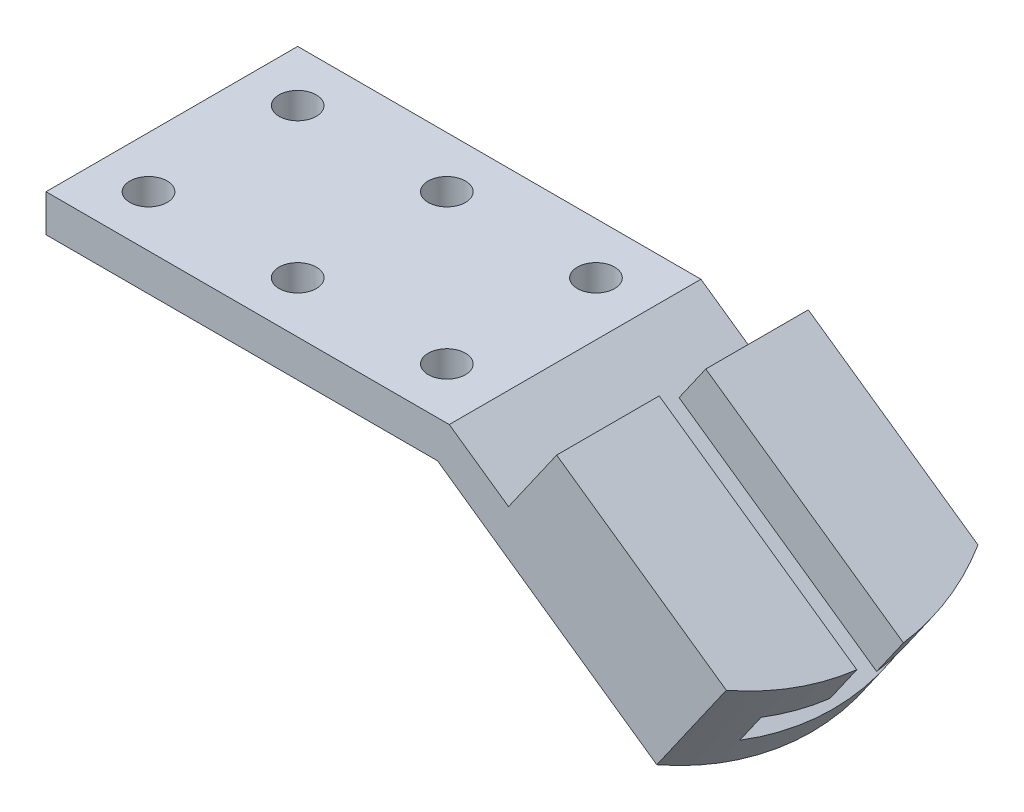
SolidWorks part; units mm, degrees
ref_plane "Front Plane" through (0, 0, 0) normal (0, 0, 1) x (1, 0, 0)
ref_plane "Top Plane" through (0, 0, 0) normal (0, 1, 0) x (1, 0, 0)
ref_plane "Right Plane" through (0, 0, 0) normal (1, 0, 0) x (0, 0, -1)
sketch "Sketch1" plane through (0, 0, 0) normal (0, 0, 1) x (1, 0, 0)
  line L0 (0, 0) -> (84, 0)
  line L1 (84, 0) -> (137.2449, -37.2825)
  line L2 (137.2449, -37.2825) -> (152.1579, -15.9845)
  line L3 (152.1579, -15.9845) -> (109.562, 13.8415)
  line L4 (109.562, 13.8415) -> (99.2376, -0.9033)
  line L5 (99.2376, -0.9033) -> (86.5224, 8)
  line L6 (86.5224, 8) -> (0, 8)
  line L7 (0, 8) -> (0, 0)
  point P3 (104.3998, 6.4691)
  dimension "D1" = 84
  dimension "D2" = 55
  dimension "D3" = 65
  dimension "D4" = 26
  dimension "D5" = 8
  dimension "D6" = 52
  dimension "D7" = 8
extrude "Boss-Extrude1" add sketch "Sketch1" along normal mid plane 54
sketch "Sketch2" plane through (0, 8, 0) normal (0, 1, 0) x (1, 0, 0)
  line L0 (86.5224, 27) -> (0, 27) construction
  line L1 (0, -27) -> (0, 27) construction
  line L2 (86.5224, -27) -> (0, -27) construction
  circle A0 centre (11, 16) radius 4
  circle A1 centre (43, 16) radius 4
  circle A2 centre (75, 16) radius 4
  circle A3 centre (43, -16) radius 4
  circle A4 centre (75, -16) radius 4
  circle A5 centre (11, -16) radius 4
  dimension "D7" = 8
  dimension "D1" = 11
  dimension "D2" = 11
  dimension "D5" = 11
  dimension "D6" = 11
  dimension "D3" = 3
  dimension "D4" = 2
extrude "Cut-Extrude1" cut sketch "Sketch2" against normal up to next
sketch "Sketch3" plane through (109.6097, -76.7496, 0) normal (0.8192, -0.5736, 0) x (0, 0, -1)
  line L5 (-27, 74.1804) -> (27, 74.1804) construction
  line L10 (-27, 56.1804) -> (32.7456, 56.1804) construction
  line L13 (-5, 74.1804) -> (5, 74.1804)
  line L14 (5, 74.1804) -> (5, 64.1804)
  line L15 (5, 64.1804) -> (17.5, 64.1804)
  line L16 (17.5, 64.1804) -> (17.5, 56.1804)
  line L17 (17.5, 56.1804) -> (-17.5, 56.1804)
  line L18 (-17.5, 56.1804) -> (-17.5, 64.1804)
  line L19 (-17.5, 64.1804) -> (-5, 64.1804)
  line L20 (-5, 64.1804) -> (-5, 74.1804)
  line L21 (0, 75.6716) -> (0, 69.4537) construction
  dimension "D1" = 10
  dimension "D2" = 35
  dimension "D3" = 10
extrude "Cut-Extrude2" cut sketch "Sketch3" against normal up to next
sketch "Sketch5" plane through (42.5481, 60.765, 0) normal (0.5736, 0.8192, 0) x (0.8192, -0.5736, 0)
  line L1 (80.2935, 0) -> (99.7758, 0) construction
  line L3 (126.2497, 27) -> (150.8663, 27)
  line L5 (126.2497, -27) -> (150.8663, -27)
  line L6 (150.8663, 27) -> (150.8663, -27)
  arc A0 (126.2497, -27) -> (126.2497, 27) centre (81.8088, 0) ccw
  dimension "D1" = 104
extrude "Cut-Extrude3" cut sketch "Sketch5" against normal up to next
